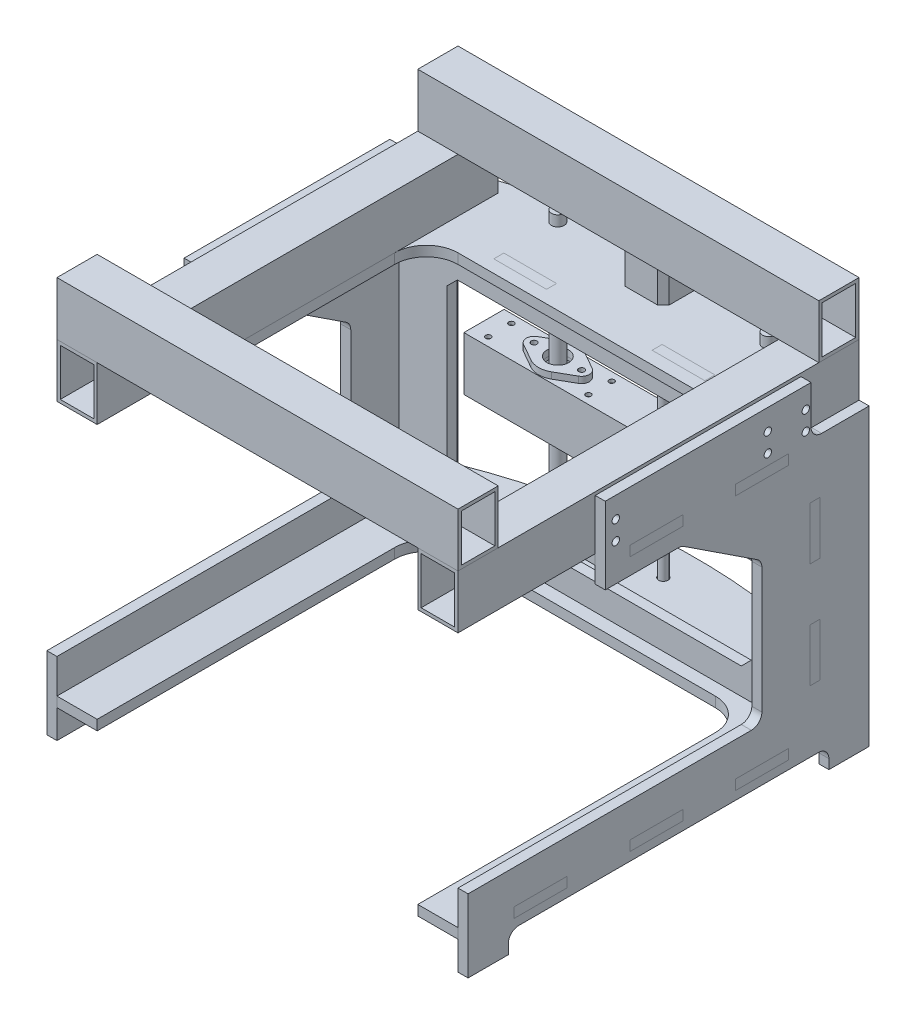
SolidWorks part; units mm, degrees
ref_plane "Front Plane" through (0, 0, 0) normal (0, 0, 1) x (1, 0, 0)
ref_plane "Top Plane" through (0, 0, 0) normal (0, 1, 0) x (1, 0, 0)
ref_plane "Right Plane" through (0, 0, 0) normal (1, 0, 0) x (0, 0, -1)
sketch "Sketch1" plane through (0, 0, 0) normal (0, 0, 1) x (1, 0, 0)
  line L0 (190, -31.5713) -> (190, 128.1143) construction
  line L1 (0, 0) -> (38.1, 0)
  line L2 (0, 0) -> (0, 50.8)
  line L3 (0, 50.8) -> (38.1, 50.8)
  line L4 (38.1, 0) -> (38.1, 50.8)
  line L5 (341.9, 0) -> (341.9, 50.8)
  line L6 (380, 50.8) -> (341.9, 50.8)
  line L7 (380, 0) -> (380, 50.8)
  line L8 (380, 0) -> (341.9, 0)
  line L9 (3.175, 47.625) -> (34.925, 47.625)
  line L10 (34.925, 3.175) -> (34.925, 47.625)
  line L11 (3.175, 3.175) -> (34.925, 3.175)
  line L12 (3.175, 3.175) -> (3.175, 47.625)
  line L13 (345.075, 3.175) -> (345.075, 47.625)
  line L14 (376.825, 47.625) -> (345.075, 47.625)
  line L15 (376.825, 3.175) -> (376.825, 47.625)
  line L16 (376.825, 3.175) -> (345.075, 3.175)
  dimension "D1" = 38.1
  dimension "D2" = 50.8
  dimension "D3" = 380
  dimension "D4" = 3.175
  dimension "D5" = 3.175
extrude "Extrude1" add sketch "Sketch1" along normal blind 380
sketch "Sketch2" plane through (0, 0, 0) normal (-1, 0, 0) x (0, 0, 1)
  line L0 (3.175, 53.975) -> (34.925, 53.975)
  line L1 (0, 50.8) -> (38.1, 50.8)
  line L2 (0, 50.8) -> (0, 101.6)
  line L3 (0, 101.6) -> (38.1, 101.6)
  line L4 (38.1, 50.8) -> (38.1, 101.6)
  line L5 (34.925, 53.975) -> (34.925, 98.425)
  line L6 (3.175, 98.425) -> (34.925, 98.425)
  line L7 (3.175, 53.975) -> (3.175, 98.425)
  line L8 (190, 50.8) -> (190, 159.3079) construction
  line L9 (380, 50.8) -> (0, 50.8) construction
  line L10 (376.825, 53.975) -> (376.825, 98.425)
  line L11 (376.825, 98.425) -> (345.075, 98.425)
  line L12 (345.075, 53.975) -> (345.075, 98.425)
  line L13 (341.9, 50.8) -> (341.9, 101.6)
  line L14 (380, 101.6) -> (341.9, 101.6)
  line L15 (380, 50.8) -> (380, 101.6)
  line L16 (380, 50.8) -> (341.9, 50.8)
  line L17 (376.825, 53.975) -> (345.075, 53.975)
  dimension "D1" = 38.1
  dimension "D2" = 50.8
  dimension "D3" = 3.175
extrude "Extrude2" add sketch "Sketch2" against normal up to surface (380 mm away) separate body up to face at (380, 25.4, 190)
sketch "Sketch3" plane through (0, 0, 0) normal (-1, 0, 0) x (0, 0, 1)
  line L0 (0, 50.8) -> (0, 0) construction
  line L1 (0, 47.8) -> (380, 47.8) construction
  line L2 (0, 47.8) -> (0, -278.4) construction
  line L3 (0, -278.4) -> (380, -278.4) construction
  line L4 (380, 47.8) -> (380, -278.4) construction
  line L5 (380, 50.8) -> (380, 0) construction
  line L6 (380, 50.8) -> (0, 50.8) construction
  line L7 (38.1, 101.6) -> (0, 101.6) construction
  line L8 (55, 47.8) -> (55, 1) construction
  line L9 (55, 1) -> (0, 1) construction
  line L10 (380, 0) -> (0, 0) construction
  line L11 (250, 47.8) -> (250, -278.4) construction
  line L12 (38.1, -278.4) -> (38.1, 47.8) construction
  line L13 (341.9, 47.8) -> (341.9, -278.4) construction
  line L14 (341.9, 101.6) -> (341.9, 50.8) construction
  line L15 (38.1, -278.4) -> (38.1, -269.35)
  line L16 (48.1, -259.35) -> (331.9, -259.35)
  line L17 (341.9, -269.35) -> (341.9, -278.4)
  line L18 (341.9, -278.4) -> (380, -278.4)
  line L19 (38.1, -278.4) -> (0, -278.4)
  line L20 (38.1, 50.8) -> (38.1, 101.6) construction
  line L21 (380, -278.4) -> (380, -209.35)
  line L22 (250, -25) -> (180.7879, -25)
  line L23 (177.8, -25) -> (177.8, -75) construction
  line L24 (111.6, -209.35) -> (380, -209.35)
  line L25 (250, -25) -> (250, 47.8)
  line L26 (55, 47.8) -> (250, 47.8)
  line L27 (55, 47.8) -> (55, 11)
  line L28 (45, 1) -> (0, 1)
  line L29 (0, 1) -> (0, -278.4)
  line L30 (177.8, -75) -> (101.6, -75) construction
  line L31 (101.6, -80.3989) -> (101.6, -199.35)
  line L32 (106.1139, -72.0381) -> (175.3018, -26.6392)
  arc A0 (45, 1) -> (55, 11) centre (45, 11) ccw
  arc A1 (106.1139, -72.0381) -> (101.6, -80.3989) centre (111.6, -80.3989) ccw
  arc A2 (180.7879, -25) -> (175.3018, -26.6392) centre (180.7879, -35) ccw
  arc A3 (111.6, -209.35) -> (101.6, -199.35) centre (111.6, -199.35) cw
  arc A4 (48.1, -259.35) -> (38.1, -269.35) centre (48.1, -269.35) ccw
  arc A5 (331.9, -259.35) -> (341.9, -269.35) centre (331.9, -269.35) cw
  point P48 (38.1, -259.35)
  point P51 (341.9, -259.35)
  dimension "D11" = 10
  dimension "D1" = 3
  dimension "D2" = 380
  dimension "D3" = 1
  dimension "D4" = 55
  dimension "D5" = 130
  dimension "D6" = 19.05
  dimension "D7" = 25
  dimension "D8" = 50
  dimension "D9" = 101.6
  dimension "D10" = 76.2
  dimension "D12" = 50
extrude "Extrude3" add sketch "Sketch3" along normal blind 9.525 separate body
sketch "Sketch7" plane through (380, 0, 0) normal (1, 0, 0) x (0, 0, -1)
  line L15 (-380, -209.35) -> (-380, -278.4)
  line L16 (-380, -278.4) -> (-341.9, -278.4)
  line L17 (-341.9, -278.4) -> (-341.9, -269.35)
  line L18 (-331.9, -259.35) -> (-48.1, -259.35)
  line L19 (-38.1, -269.35) -> (-38.1, -278.4)
  line L20 (-38.1, -278.4) -> (0, -278.4)
  line L21 (0, -278.4) -> (0, 1)
  line L22 (0, 1) -> (-45, 1)
  line L23 (-55, 11) -> (-55, 47.8)
  line L24 (-55, 47.8) -> (-250, 47.8)
  line L25 (-250, 47.8) -> (-250, -25)
  line L26 (-250, -25) -> (-180.7879, -25)
  line L27 (-175.3018, -26.6392) -> (-106.1139, -72.0381)
  line L28 (-101.6, -80.3989) -> (-101.6, -199.35)
  line L29 (-111.6, -209.35) -> (-380, -209.35)
  line L30 (-380, -209.35) -> (-380, -278.4)
  line L31 (-380, -278.4) -> (-341.9, -278.4)
  line L32 (-341.9, -278.4) -> (-341.9, -269.35)
  line L33 (-331.9, -259.35) -> (-48.1, -259.35)
  line L34 (-38.1, -269.35) -> (-38.1, -278.4)
  line L35 (-38.1, -278.4) -> (0, -278.4)
  line L36 (0, -278.4) -> (0, 1)
  line L37 (0, 1) -> (-45, 1)
  line L38 (-55, 11) -> (-55, 47.8)
  line L39 (-55, 47.8) -> (-250, 47.8)
  line L40 (-250, 47.8) -> (-250, -25)
  line L41 (-250, -25) -> (-180.7879, -25)
  line L42 (-175.3018, -26.6392) -> (-106.1139, -72.0381)
  line L43 (-101.6, -80.3989) -> (-101.6, -199.35)
  line L44 (-111.6, -209.35) -> (-380, -209.35)
  arc A6 (-331.9, -259.35) -> (-341.9, -269.35) centre (-331.9, -269.35) ccw
  arc A7 (-38.1, -269.35) -> (-48.1, -259.35) centre (-48.1, -269.35) ccw
  arc A8 (-55, 11) -> (-45, 1) centre (-45, 11) ccw
  arc A9 (-175.3018, -26.6392) -> (-180.7879, -25) centre (-180.7879, -35) ccw
  arc A10 (-101.6, -80.3989) -> (-106.1139, -72.0381) centre (-111.6, -80.3989) ccw
  arc A11 (-111.6, -209.35) -> (-101.6, -199.35) centre (-111.6, -199.35) ccw
  arc A12 (-331.9, -259.35) -> (-341.9, -269.35) centre (-331.9, -269.35) ccw
  arc A13 (-38.1, -269.35) -> (-48.1, -259.35) centre (-48.1, -269.35) ccw
  arc A14 (-55, 11) -> (-45, 1) centre (-45, 11) ccw
  arc A15 (-175.3018, -26.6392) -> (-180.7879, -25) centre (-180.7879, -35) ccw
  arc A16 (-101.6, -80.3989) -> (-106.1139, -72.0381) centre (-111.6, -80.3989) ccw
  arc A17 (-111.6, -209.35) -> (-101.6, -199.35) centre (-111.6, -199.35) ccw
  dimension "D1" = 0
extrude "Extrude5" add sketch "Sketch7" along normal blind 9.525 separate body
sketch "Sketch8" plane through (-9.525, 0, 0) normal (-1, 0, 0) x (0, 0, 1)
  line L0 (380, 0) -> (0, 0) construction
  line L1 (380, 0) -> (0, 0) construction
  line L2 (106.1139, -72.0381) -> (201.3839, -9.525) construction
  line L3 (226.3839, 0) -> (176.3839, 0)
  line L4 (226.3839, 0) -> (226.3839, -9.525)
  line L5 (226.3839, -9.525) -> (176.3839, -9.525)
  line L6 (176.3839, 0) -> (176.3839, -9.525)
  line L7 (76.3839, 0) -> (126.3839, 0)
  line L8 (76.3839, 0) -> (76.3839, -9.525)
  line L9 (76.3839, -9.525) -> (126.3839, -9.525)
  line L10 (126.3839, 0) -> (126.3839, -9.525)
  line L11 (106.1139, -72.0381) -> (175.3018, -26.6392) construction
  line L13 (176.3839, -9.525) -> (176.3839, -259.35) construction
  line L14 (48.1, -259.35) -> (331.9, -259.35) construction
  line L15 (226.3839, -9.525) -> (226.3839, -259.35) construction
  line L16 (76.3839, -9.525) -> (76.3839, -259.35) construction
  line L17 (126.3839, -9.525) -> (126.3839, -259.35) construction
  line L18 (0, -251.35) -> (380, -251.35) construction
  line L19 (0, 1) -> (0, -278.4) construction
  line L20 (380, -278.4) -> (380, -209.35) construction
  line L21 (286.3839, -251.35) -> (336.3839, -251.35)
  line L22 (76.3839, -251.35) -> (126.3839, -251.35)
  line L23 (76.3839, -251.35) -> (76.3839, -241.825)
  line L24 (76.3839, -241.825) -> (126.3839, -241.825)
  line L25 (126.3839, -251.35) -> (126.3839, -241.825)
  line L26 (176.3839, -251.35) -> (226.3839, -251.35)
  line L27 (176.3839, -251.35) -> (176.3839, -241.825)
  line L28 (176.3839, -241.825) -> (226.3839, -241.825)
  line L29 (226.3839, -251.35) -> (226.3839, -241.825)
  line L30 (286.3839, -251.35) -> (286.3839, -241.825)
  line L31 (286.3839, -241.825) -> (336.3839, -241.825)
  line L32 (336.3839, -251.35) -> (336.3839, -241.825)
  dimension "D1" = 9.525
  dimension "D2" = 50
  dimension "D3" = 50
  dimension "D4" = 50
  dimension "D5" = 8
  dimension "D6" = 9.525
  dimension "D7" = 60
  dimension "D8" = 50
extrude "Cut-Extrude1" cut sketch "Sketch8" against normal through all
sketch "Sketch9" plane through (0, 0, 0) normal (0, -1, 0) x (1, 0, 0)
  line L0 (190, -35.95) -> (190, 250) construction
  line L1 (0, 250) -> (38.1, 250)
  line L2 (0, 250) -> (0, 226.3839)
  line L3 (0, 0) -> (380, 0) construction
  line L4 (380, 250) -> (380, 226.3839)
  line L5 (-9.525, 19.05) -> (389.525, 19.05) construction
  line L6 (-9.525, 0) -> (-9.525, 38.1) construction
  line L7 (389.525, 38.1) -> (389.525, 0) construction
  line L8 (38.1, 250) -> (38.1, 98.1)
  line L9 (38.1, 380) -> (38.1, 0) construction
  line L10 (380, 38.1) -> (0, 38.1) construction
  line L11 (68.1, 68.1) -> (311.9, 68.1)
  line L12 (341.9, 380) -> (341.9, 0) construction
  line L13 (341.9, 98.1) -> (341.9, 250)
  line L14 (341.9, 250) -> (380, 250)
  line L15 (380, 176.3839) -> (380, 126.3839)
  line L16 (380, 76.3839) -> (380, 0)
  line L17 (0, 176.3839) -> (0, 126.3839)
  line L18 (0, 76.3839) -> (0, 0)
  line L19 (0, 176.3839) -> (0, 226.3839)
  line L20 (0, 226.3839) -> (-9.525, 226.3839)
  line L21 (-9.525, 226.3839) -> (-9.525, 176.3839)
  line L22 (-9.525, 176.3839) -> (0, 176.3839)
  line L24 (0, 226.3839) -> (-9.525, 226.3839)
  line L25 (-9.525, 226.3839) -> (-9.525, 176.3839)
  line L26 (-9.525, 176.3839) -> (0, 176.3839)
  line L27 (0, 76.3839) -> (0, 126.3839)
  line L28 (0, 126.3839) -> (-9.525, 126.3839)
  line L29 (-9.525, 126.3839) -> (-9.525, 76.3839)
  line L30 (-9.525, 76.3839) -> (0, 76.3839)
  line L32 (0, 126.3839) -> (-9.525, 126.3839)
  line L33 (-9.525, 126.3839) -> (-9.525, 76.3839)
  line L34 (-9.525, 76.3839) -> (0, 76.3839)
  line L35 (380, 176.3839) -> (389.525, 176.3839)
  line L36 (389.525, 176.3839) -> (389.525, 226.3839)
  line L37 (389.525, 226.3839) -> (380, 226.3839)
  line L38 (380, 226.3839) -> (380, 176.3839)
  line L39 (380, 176.3839) -> (389.525, 176.3839)
  line L40 (389.525, 176.3839) -> (389.525, 226.3839)
  line L41 (389.525, 226.3839) -> (380, 226.3839)
  line L43 (380, 76.3839) -> (389.525, 76.3839)
  line L44 (389.525, 76.3839) -> (389.525, 126.3839)
  line L45 (389.525, 126.3839) -> (380, 126.3839)
  line L46 (380, 126.3839) -> (380, 76.3839)
  line L47 (380, 76.3839) -> (389.525, 76.3839)
  line L48 (389.525, 76.3839) -> (389.525, 126.3839)
  line L49 (389.525, 126.3839) -> (380, 126.3839)
  arc A0 (0, 0) -> (380, 0) centre (190, 484.1112) ccw
  arc A1 (68.1, 68.1) -> (38.1, 98.1) centre (68.1, 98.1) cw
  arc A2 (311.9, 68.1) -> (341.9, 98.1) centre (311.9, 98.1) ccw
  point P7 (190, -35.95)
  point P27 (38.1, 68.1)
  point P28 (38.1, 38.1)
  point P31 (341.9, 38.1)
  point P49 (341.9, 68.1)
  dimension "D2" = 30
  dimension "D7" = 30
  dimension "D1" = 55
  dimension "D3" = 0
  dimension "D4" = 0
  dimension "D5" = 0
  dimension "D6" = 0
extrude "Extrude6" add sketch "Sketch9" along normal up to surface (9.525 mm away) separate body up to face at (-4.7625, -9.525, 101.3839)
sketch "Sketch10" plane through (0, -251.35, 0) normal (0, 1, 0) x (1, 0, 0)
  line L0 (0, -250) -> (0, -286.3839)
  line L1 (38.1, -250) -> (38.1, -336.3839)
  line L3 (341.9, -250) -> (341.9, -336.3839)
  line L4 (0, -336.3839) -> (0, -286.3839)
  line L5 (0, -286.3839) -> (-9.525, -286.3839)
  line L6 (-9.525, -286.3839) -> (-9.525, -336.3839)
  line L7 (-9.525, -336.3839) -> (0, -336.3839)
  line L8 (38.1, -336.3839) -> (38.1, -380)
  line L9 (0, -286.3839) -> (-9.525, -286.3839)
  line L10 (-9.525, -286.3839) -> (-9.525, -336.3839)
  line L11 (-9.525, -336.3839) -> (0, -336.3839)
  line L12 (380, -336.3839) -> (389.525, -336.3839)
  line L13 (389.525, -336.3839) -> (389.525, -286.3839)
  line L14 (389.525, -286.3839) -> (380, -286.3839)
  line L15 (380, -286.3839) -> (380, -336.3839)
  line L16 (380, -336.3839) -> (389.525, -336.3839)
  line L17 (389.525, -336.3839) -> (389.525, -286.3839)
  line L18 (389.525, -286.3839) -> (380, -286.3839)
  line L19 (38.1, -380) -> (0, -380)
  line L20 (341.9, -380) -> (341.9, 0) construction
  line L22 (380, -286.3839) -> (380, -250)
  line L23 (0, -250) -> (38.1, -250)
  line L24 (0, -226.3839) -> (0, -250)
  line L25 (-9.525, -226.3839) -> (0, -226.3839)
  line L26 (-9.525, -176.3839) -> (-9.525, -226.3839)
  line L27 (0, -176.3839) -> (-9.525, -176.3839)
  line L28 (0, -126.3839) -> (0, -176.3839)
  line L29 (-9.525, -126.3839) -> (0, -126.3839)
  line L30 (-9.525, -76.3839) -> (-9.525, -126.3839)
  line L31 (0, -76.3839) -> (-9.525, -76.3839)
  line L32 (0, 0) -> (0, -76.3839)
  line L33 (380, -76.3839) -> (380, 0)
  line L34 (389.525, -76.3839) -> (380, -76.3839)
  line L35 (389.525, -126.3839) -> (389.525, -76.3839)
  line L36 (380, -126.3839) -> (389.525, -126.3839)
  line L37 (380, -176.3839) -> (380, -126.3839)
  line L38 (389.525, -176.3839) -> (380, -176.3839)
  line L39 (389.525, -226.3839) -> (389.525, -176.3839)
  line L40 (380, -226.3839) -> (389.525, -226.3839)
  line L41 (380, -250) -> (380, -226.3839)
  line L42 (341.9, -250) -> (380, -250)
  line L43 (341.9, -98.1) -> (341.9, -250)
  line L44 (68.1, -68.1) -> (311.9, -68.1)
  line L45 (38.1, -250) -> (38.1, -98.1)
  line L46 (0, -380) -> (0, -336.3839)
  line L47 (0, -226.3839) -> (0, -250)
  line L48 (-9.525, -226.3839) -> (0, -226.3839)
  line L49 (-9.525, -176.3839) -> (-9.525, -226.3839)
  line L50 (0, -176.3839) -> (-9.525, -176.3839)
  line L51 (0, -126.3839) -> (0, -176.3839)
  line L52 (-9.525, -126.3839) -> (0, -126.3839)
  line L53 (-9.525, -76.3839) -> (-9.525, -126.3839)
  line L54 (0, -76.3839) -> (-9.525, -76.3839)
  line L55 (0, 0) -> (0, -76.3839)
  line L56 (380, -76.3839) -> (380, 0)
  line L57 (389.525, -76.3839) -> (380, -76.3839)
  line L58 (389.525, -126.3839) -> (389.525, -76.3839)
  line L59 (380, -126.3839) -> (389.525, -126.3839)
  line L60 (380, -176.3839) -> (380, -126.3839)
  line L61 (389.525, -176.3839) -> (380, -176.3839)
  line L62 (389.525, -226.3839) -> (389.525, -176.3839)
  line L63 (380, -226.3839) -> (389.525, -226.3839)
  line L64 (380, -250) -> (380, -226.3839)
  line L65 (341.9, -336.3839) -> (341.9, -380)
  line L66 (341.9, -98.1) -> (341.9, -250)
  line L67 (68.1, -68.1) -> (311.9, -68.1)
  line L68 (38.1, -250) -> (38.1, -98.1)
  line L69 (380, -380) -> (0, -380) construction
  line L70 (341.9, -380) -> (380, -380)
  line L71 (380, -380) -> (380, -336.3839)
  arc A3 (380, 0) -> (0, 0) centre (190, -484.1112) ccw
  arc A4 (341.9, -98.1) -> (311.9, -68.1) centre (311.9, -98.1) ccw
  arc A5 (68.1, -68.1) -> (38.1, -98.1) centre (68.1, -98.1) ccw
  arc A6 (380, 0) -> (0, 0) centre (190, -484.1112) ccw
  arc A7 (341.9, -98.1) -> (311.9, -68.1) centre (311.9, -98.1) ccw
  arc A8 (68.1, -68.1) -> (38.1, -98.1) centre (68.1, -98.1) ccw
  dimension "D1" = 0
  dimension "D2" = 0
  dimension "D3" = 0
extrude "Extrude7" add sketch "Sketch10" along normal up to surface (9.525 mm away) separate body up to face at (-4.7625, -241.825, 101.3839)
sketch "Sketch11" plane through (0, 0, 0) normal (0, 1, 0) x (1, 0, 0)
  line L0 (190, -380) -> (190, 35.95) construction
  line L1 (380, -380) -> (0, -380) construction
  line L2 (168.85, 4.6) -> (211.15, 4.6) construction
  line L3 (168.85, 25.75) -> (211.15, 25.75) construction
  line L4 (168.85, 25.75) -> (168.85, -16.55) construction
  line L5 (168.85, -16.55) -> (211.15, -16.55) construction
  line L6 (211.15, 25.75) -> (211.15, -16.55) construction
  line L7 (174.5, 20.1) -> (205.5, 20.1) construction
  line L8 (205.5, 20.1) -> (205.5, -10.9) construction
  line L9 (174.5, -10.9) -> (205.5, -10.9) construction
  line L10 (174.5, 20.1) -> (174.5, -10.9) construction
  line L11 (0, -19.05) -> (380, -19.05) construction
  line L17 (380, -38.1) -> (380, 0)
  line L18 (380, 0) -> (0, 0)
  line L19 (0, 0) -> (0, -38.1)
  line L20 (0, -38.1) -> (380, -38.1)
  line L21 (380, -38.1) -> (380, 0) construction
  line L22 (380, 0) -> (0, 0) construction
  line L23 (0, 0) -> (0, -38.1) construction
  line L24 (0, -38.1) -> (380, -38.1) construction
  arc A0 (380, 0) -> (0, 0) centre (190, -484.1112) ccw construction
  circle A1 centre (190, 4.6) radius 12
  circle A2 centre (90, 4.6) radius 6
  circle A3 centre (290, 4.6) radius 6
  point P11 (190, 25.75)
  dimension "D5" = 24
  dimension "D6" = 12
  dimension "D1" = 42.3
  dimension "D2" = 31
  dimension "D3" = 0
  dimension "D4" = 2.5
  dimension "D7" = 200
extrude "Cut-Extrude2" cut sketch "Sketch11" against normal up to next (9.525 mm away)
sketch "Sketch12" plane through (0, -241.825, 0) normal (0, 1, 0) x (1, 0, 0)
  circle A0 centre (90, 4.6) radius 6 construction
  circle A1 centre (190, 4.6) radius 12 construction
  circle A2 centre (290, 4.6) radius 6 construction
  circle A3 centre (90, 4.6) radius 6
  circle A4 centre (190, 4.6) radius 12 construction
  circle A5 centre (290, 4.6) radius 6
  circle A6 centre (190, 4.6) radius 4.5
  dimension "D1" = 9
extrude "Cut-Extrude3" cut sketch "Sketch12" against normal up to next (9.525 mm away)
sketch "Sketch13" plane through (0, 0, 0) normal (0, 1, 0) x (1, 0, 0)
  line L0 (174.5, 25.6) -> (169, 20.1)
  line L1 (174.5, 25.6) -> (205.5, 25.6)
  line L2 (169, 20.1) -> (169, -10.9)
  line L3 (174.5, -16.4) -> (205.5, -16.4)
  line L4 (211, 20.1) -> (211, -10.9)
  line L5 (205.5, 25.6) -> (211, 20.1)
  line L6 (211, -10.9) -> (205.5, -16.4)
  line L7 (169, -10.9) -> (174.5, -16.4)
  line L8 (169, 4.6) -> (211, 4.6) construction
  circle A4 centre (190, 4.6) radius 4.5 construction
  point P0 (169, 25.6)
  point P1 (211, -16.4)
  point P2 (169, -16.4)
  point P3 (211, 25.6)
  point P14 (190, 4.6)
  dimension "D1" = 42
  dimension "D4" = 5.5
  dimension "D5" = 5.5
  dimension "D6" = 5.5
  dimension "D7" = 5.5
extrude "Extrude8" add sketch "Sketch13" along normal blind 48 separate body
sketch "Sketch14" plane through (0, 0, 0) normal (0, 1, 0) x (1, 0, 0)
  circle A0 centre (90, 4.6) radius 6 construction
  circle A1 centre (290, 4.6) radius 6 construction
  circle A2 centre (90, 4.6) radius 6
  circle A3 centre (290, 4.6) radius 6
extrude "Extrude9" add sketch "Sketch14" along normal blind 10 and the other way offset from surface (259.35 mm away) 8 separate body other way up to face at (190, -251.35, -0.1)
sketch "Sketch15" plane through (0, -251.35, 0) normal (0, -1, 0) x (1, 0, 0)
  circle A0 centre (190, -4.6) radius 4
  dimension "D1" = 8
extrude "Extrude10" add sketch "Sketch15" against normal up to surface (251.35 mm away) separate body up to face at (190, 0, -4.6)
sketch "Sketch16" plane through (0, 0, 0) normal (0, 1, 0) x (1, 0, 0)
  line L0 (38.1, -56.1) -> (341.9, -56.1) construction
  line L1 (38.1, -380) -> (38.1, 0) construction
  line L2 (341.9, -380) -> (341.9, 0) construction
  line L4 (311.9, -68.1) -> (68.1, -68.1) construction
  line L5 (190, 0) -> (190, -380) construction
  line L6 (90, -56.1) -> (140, -56.1)
  line L7 (90, -56.1) -> (90, -46.575)
  line L8 (90, -46.575) -> (140, -46.575)
  line L9 (140, -56.1) -> (140, -46.575)
  line L10 (380, 0) -> (0, 0) construction
  line L11 (380, -380) -> (0, -380) construction
  line L12 (240, -56.1) -> (240, -46.575)
  line L13 (290, -56.1) -> (240, -56.1)
  line L14 (290, -56.1) -> (290, -46.575)
  line L15 (290, -46.575) -> (240, -46.575)
  dimension "D1" = 12
  dimension "D2" = 50
  dimension "D3" = 9.525
  dimension "D4" = 50
extrude "Cut-Extrude4" cut sketch "Sketch16" against normal through all
sketch "Sketch17" plane through (-9.525, 0, 0) normal (-1, 0, 0) x (0, 0, 1)
  line L0 (46.575, -9.525) -> (46.575, -241.825) construction
  line L1 (56.1, -9.525) -> (56.1, -241.825) construction
  line L2 (46.575, -125.675) -> (91.0114, -125.675) construction
  line L3 (56.1, -100.675) -> (56.1, -50.675)
  line L4 (46.575, -9.525) -> (56.1, -9.525)
  line L5 (56.1, -9.525) -> (56.1, 0)
  line L6 (56.1, 0) -> (46.575, 0)
  line L7 (46.575, 0) -> (46.575, -9.525)
  line L8 (46.575, -9.525) -> (56.1, -9.525) construction
  line L9 (56.1, -9.525) -> (56.1, 0) construction
  line L10 (56.1, 0) -> (46.575, 0) construction
  line L11 (46.575, 0) -> (46.575, -9.525) construction
  line L12 (46.575, -50.675) -> (56.1, -50.675)
  line L13 (46.575, -100.675) -> (46.575, -50.675)
  line L14 (46.575, -100.675) -> (56.1, -100.675)
  line L15 (46.575, -150.675) -> (56.1, -150.675)
  line L16 (46.575, -150.675) -> (46.575, -200.675)
  line L17 (46.575, -200.675) -> (56.1, -200.675)
  line L18 (56.1, -150.675) -> (56.1, -200.675)
  line L22 (56.1, -251.35) -> (56.1, -241.825)
  line L23 (56.1, -241.825) -> (46.575, -241.825)
  line L24 (46.575, -241.825) -> (46.575, -251.35)
  line L25 (46.575, -251.35) -> (56.1, -251.35)
  line L26 (56.1, -251.35) -> (56.1, -241.825) construction
  line L27 (56.1, -241.825) -> (46.575, -241.825) construction
  line L28 (46.575, -241.825) -> (46.575, -251.35) construction
  line L29 (46.575, -251.35) -> (56.1, -251.35) construction
  dimension "D3" = 50
  dimension "D4" = 50
  dimension "D1" = 0
  dimension "D2" = 0
extrude "Cut-Extrude5" cut sketch "Sketch17" against normal through all
sketch "Sketch18" plane through (0, 0, 46.575) normal (0, 0, 1) x (1, 0, 0)
  line L0 (0, -9.525) -> (90, -9.525)
  line L1 (380, -9.525) -> (380, -50.675)
  line L2 (380, -241.825) -> (290, -241.825)
  line L3 (0, -241.825) -> (0, -200.675)
  line L4 (380, -100.675) -> (380, -150.675)
  line L5 (380, -200.675) -> (380, -241.825)
  line L6 (240, -241.825) -> (140, -241.825)
  line L7 (90, -241.825) -> (0, -241.825)
  line L8 (240, -9.525) -> (290, -9.525)
  line L9 (290, -9.525) -> (290, 0)
  line L10 (290, 0) -> (240, 0)
  line L11 (240, 0) -> (240, -9.525)
  line L13 (290, -9.525) -> (290, 0)
  line L14 (290, 0) -> (240, 0)
  line L15 (240, 0) -> (240, -9.525)
  line L16 (90, -9.525) -> (140, -9.525)
  line L17 (140, -9.525) -> (140, 0)
  line L18 (140, 0) -> (90, 0)
  line L19 (90, 0) -> (90, -9.525)
  line L20 (290, -9.525) -> (380, -9.525)
  line L21 (140, -9.525) -> (140, 0)
  line L22 (140, 0) -> (90, 0)
  line L23 (90, 0) -> (90, -9.525)
  line L24 (0, -100.675) -> (0, -50.675)
  line L25 (0, -50.675) -> (-9.525, -50.675)
  line L26 (-9.525, -50.675) -> (-9.525, -100.675)
  line L27 (-9.525, -100.675) -> (0, -100.675)
  line L28 (140, -9.525) -> (240, -9.525)
  line L29 (0, -50.675) -> (-9.525, -50.675)
  line L30 (-9.525, -50.675) -> (-9.525, -100.675)
  line L31 (-9.525, -100.675) -> (0, -100.675)
  line L32 (0, -200.675) -> (0, -150.675)
  line L33 (0, -150.675) -> (-9.525, -150.675)
  line L34 (-9.525, -150.675) -> (-9.525, -200.675)
  line L35 (-9.525, -200.675) -> (0, -200.675)
  line L36 (0, -50.675) -> (0, -9.525)
  line L37 (0, -150.675) -> (-9.525, -150.675)
  line L38 (-9.525, -150.675) -> (-9.525, -200.675)
  line L39 (-9.525, -200.675) -> (0, -200.675)
  line L40 (140, -251.35) -> (140, -241.825)
  line L41 (140, -241.825) -> (90, -241.825)
  line L42 (90, -241.825) -> (90, -251.35)
  line L43 (90, -251.35) -> (140, -251.35)
  line L44 (140, -251.35) -> (140, -241.825)
  line L45 (0, -150.675) -> (0, -100.675)
  line L46 (90, -241.825) -> (90, -251.35)
  line L47 (90, -251.35) -> (140, -251.35)
  line L48 (290, -251.35) -> (290, -241.825)
  line L49 (290, -241.825) -> (240, -241.825)
  line L50 (240, -241.825) -> (240, -251.35)
  line L51 (240, -251.35) -> (290, -251.35)
  line L52 (290, -251.35) -> (290, -241.825)
  line L54 (240, -241.825) -> (240, -251.35)
  line L55 (240, -251.35) -> (290, -251.35)
  line L56 (380, -200.675) -> (389.525, -200.675)
  line L57 (389.525, -200.675) -> (389.525, -150.675)
  line L58 (389.525, -150.675) -> (380, -150.675)
  line L59 (380, -150.675) -> (380, -200.675)
  line L60 (380, -200.675) -> (389.525, -200.675)
  line L61 (389.525, -200.675) -> (389.525, -150.675)
  line L62 (389.525, -150.675) -> (380, -150.675)
  line L64 (380, -100.675) -> (389.525, -100.675)
  line L65 (389.525, -100.675) -> (389.525, -50.675)
  line L66 (389.525, -50.675) -> (380, -50.675)
  line L67 (380, -50.675) -> (380, -100.675)
  line L68 (380, -100.675) -> (389.525, -100.675)
  line L69 (389.525, -100.675) -> (389.525, -50.675)
  line L70 (389.525, -50.675) -> (380, -50.675)
  dimension "D1" = 0
  dimension "D2" = 0
  dimension "D3" = 0
  dimension "D4" = 0
  dimension "D5" = 0
  dimension "D6" = 0
  dimension "D7" = 0
  dimension "D8" = 0
extrude "Extrude11" add sketch "Sketch18" along normal up to surface (9.525 mm away) separate body up to face at (-4.7625, -175.675, 56.1)
sketch "Sketch20" plane through (0, 0, 46.575) normal (0, 0, -1) x (-1, 0, 0)
  line L0 (-190, 0) -> (-190, -251.35) construction
  line L3 (0, 0) -> (-380, 0) construction
  line L6 (-380, -251.35) -> (0, -251.35) construction
  line L10 (-264.5, -34.525) -> (-255.5, -34.525)
  line L11 (-264.5, -34.525) -> (-264.5, -216.825)
  line L12 (-264.5, -216.825) -> (-255.5, -216.825)
  line L13 (-255.5, -34.525) -> (-255.5, -216.825)
  line L15 (-260, -34.525) -> (-260, -216.825) construction
  line L17 (-334.5, -34.525) -> (-325.5, -34.525)
  line L18 (-334.5, -34.525) -> (-334.5, -216.825)
  line L19 (-334.5, -216.825) -> (-325.5, -216.825)
  line L20 (-325.5, -34.525) -> (-325.5, -216.825)
  line L21 (-330, -34.525) -> (-330, -216.825) construction
  line L22 (-54.5, -34.525) -> (-54.5, -216.825)
  line L23 (-45.5, -216.825) -> (-54.5, -216.825)
  line L24 (-45.5, -34.525) -> (-45.5, -216.825)
  line L25 (-45.5, -34.525) -> (-54.5, -34.525)
  line L26 (-124.5, -34.525) -> (-124.5, -216.825)
  line L27 (-115.5, -216.825) -> (-124.5, -216.825)
  line L28 (-115.5, -34.525) -> (-115.5, -216.825)
  line L29 (-115.5, -34.525) -> (-124.5, -34.525)
  line L30 (-380, -9.525) -> (0, -9.525) construction
  line L31 (-290, -241.825) -> (-380, -241.825) construction
  line L32 (-190, -125.675) -> (-138.6415, -125.675) construction
  line L33 (-200, -50.675) -> (-180, -50.675)
  line L34 (-215, -65.675) -> (-215, -185.675)
  line L35 (-200, -200.675) -> (-180, -200.675)
  line L36 (-165, -65.675) -> (-165, -185.675)
  arc A0 (-200, -50.675) -> (-215, -65.675) centre (-200, -65.675) ccw
  arc A1 (-165, -65.675) -> (-180, -50.675) centre (-180, -65.675) ccw
  arc A2 (-180, -200.675) -> (-165, -185.675) centre (-180, -185.675) ccw
  arc A3 (-200, -200.675) -> (-215, -185.675) centre (-200, -185.675) cw
  point P38 (-215, -50.675)
  point P45 (-215, -200.675)
  dimension "D9" = 15
  dimension "D1" = 9
  dimension "D2" = 9
  dimension "D3" = 70
  dimension "D4" = 70
  dimension "D5" = 25
  dimension "D6" = 25
  dimension "D7" = 50
  dimension "D8" = 150
extrude "Cut-Extrude7" cut sketch "Sketch20" against normal through all
sketch "Sketch21" plane through (-9.525, 0, 0) normal (-1, 0, 0) x (0, 0, 1)
  line L0 (380, 0) -> (0, 0) construction
  line L1 (380, 0) -> (0, 0) construction
  line L2 (60, 50.8) -> (60, 0) construction
  line L3 (380, 50.8) -> (0, 50.8) construction
  line L4 (96, 50.8) -> (96, 0) construction
  line L5 (0, 28) -> (380, 28) construction
  line L6 (0, 50.8) -> (0, 0) construction
  line L7 (380, 50.8) -> (380, 0) construction
  line L8 (0, 10) -> (380, 10) construction
  line L9 (240, 50.8) -> (240, 0) construction
  circle A0 centre (60, 28) radius 3.5
  circle A1 centre (60, 10) radius 3.5
  circle A2 centre (96, 28) radius 3.5
  circle A3 centre (96, 10) radius 3.5
  circle A4 centre (240, 28) radius 3.5
  circle A5 centre (240, 10) radius 3.5
  dimension "D1" = 7
  dimension "D2" = 10
  dimension "D3" = 18
  dimension "D4" = 60
  dimension "D5" = 36
  dimension "D6" = 180
extrude "Cut-Extrude8" cut sketch "Sketch21" against normal through all
sketch "Sketch22" plane through (0, 0, 56.1) normal (0, 0, 1) x (1, 0, 0)
  line L1 (45.5, -34.525) -> (334.5, -34.525)
  line L2 (45.5, -34.525) -> (45.5, -216.825)
  line L3 (45.5, -216.825) -> (334.5, -216.825)
  line L4 (334.5, -34.525) -> (334.5, -216.825)
extrude "Cut-Extrude9" cut sketch "Sketch22" against normal through all
chamfer "Chamfer1" distance 10 angle 45 4 edges at (45.5, -216.825, 51.3375) (334.5, -216.825, 51.3375) (334.5, -34.525, 51.3375) (45.5, -34.525, 51.3375)
ref_point "Point1"
ref_plane "Mid-Plane" through (190, 0, 0) normal (-1, 0, 0) x (0, 0, 1)
sketch "Sketch23" plane through (190, 0, 0) normal (-1, 0, 0) x (0, 0, 1)
  line L0 (-4.6, 10) -> (-4.6, -262.0924) construction
  line L1 (1.4, 10) -> (-10.6, 10) construction
  line L2 (-20.475, -119.4974) -> (11.275, -119.4974)
  line L3 (-23.65, -116.3224) -> (14.45, -116.3224)
  line L4 (-23.65, -116.3224) -> (-23.65, -167.1224)
  line L5 (-23.65, -167.1224) -> (14.45, -167.1224)
  line L6 (14.45, -116.3224) -> (14.45, -167.1224)
  line L7 (11.275, -119.4974) -> (11.275, -163.9474)
  line L8 (-20.475, -163.9474) -> (11.275, -163.9474)
  line L9 (-20.475, -119.4974) -> (-20.475, -163.9474)
  dimension "D1" = 50.8
  dimension "D2" = 38.1
  dimension "D3" = 3.175
extrude "Extrude12" add sketch "Sketch23" along normal mid plane 340 separate body
sketch "Sketch28" plane through (0, -116.3224, 0) normal (0, 1, 0) x (1, 0, 0)
  line L0 (190, 23.65) -> (190, -17.3758) construction
  line L1 (20, 23.65) -> (360, 23.65) construction
  line L2 (290, 23.65) -> (290, -14.45) construction
  line L3 (20, -14.45) -> (360, -14.45) construction
  line L4 (90, 23.65) -> (90, -14.45) construction
  line L5 (360, 4.6) -> (20, 4.6) construction
  line L6 (360, -14.45) -> (360, 23.65) construction
  line L7 (20, -14.45) -> (20, 23.65) construction
  line L9 (290.5, -6) -> (289.5, -6)
  line L10 (290.5, -6) -> (290.5, 15.2) construction
  line L11 (290.5, 15.2) -> (289.5, 15.2)
  line L12 (289.5, -6) -> (289.5, 15.2) construction
  circle A0 centre (290, 4.6) radius 6 construction
  circle A1 centre (90, 4.6) radius 6 construction
  circle A2 centre (290, 4.6) radius 6 construction
  circle A3 centre (90, 4.6) radius 6 construction
  circle A4 centre (90, 4.6) radius 10.6
  arc A5 (289.5, 15.2) -> (289.5, -6) centre (289.5, 4.6) ccw
  arc A6 (290.5, -6) -> (290.5, 15.2) centre (290.5, 4.6) ccw
  circle A7 centre (312.5, 4.6) radius 2
  circle A8 centre (267.5, 4.6) radius 2
  circle A9 centre (67.5, 4.6) radius 2
  circle A10 centre (112.5, 4.6) radius 2
  circle A11 centre (190, 4.6) radius 14
  dimension "D1" = 21.2
  dimension "D4" = 4
  dimension "D6" = 28
  dimension "D2" = 1
  dimension "D3" = 21.2
  dimension "D5" = 45
extrude "Cut-Extrude13" cut sketch "Sketch28" against normal up to next (3.175 mm away)
sketch "Sketch29" plane through (0, -167.1224, 0) normal (0, -1, 0) x (1, 0, 0)
  line L0 (290, -23.65) -> (290, 14.45) construction
  line L1 (20, -23.65) -> (360, -23.65) construction
  line L2 (20, 14.45) -> (360, 14.45) construction
  line L3 (190, -23.65) -> (190, 14.45) construction
  line L4 (360, -4.6) -> (20, -4.6) construction
  line L5 (360, -23.65) -> (360, 14.45) construction
  line L6 (20, -23.65) -> (20, 14.45) construction
  circle A0 centre (190, -4.6) radius 4 construction
  circle A1 centre (90, -4.6) radius 6 construction
  circle A2 centre (290, -4.6) radius 6 construction
  circle A3 centre (190, -4.6) radius 4 construction
  circle A4 centre (90, -4.6) radius 6 construction
  circle A5 centre (290, -4.6) radius 6 construction
  circle A6 centre (290, -4.6) radius 11
  circle A7 centre (312.5, -4.6) radius 2
  circle A8 centre (190, -4.6) radius 8
  circle A9 centre (267.5, -4.6) radius 2
  circle A10 centre (112.5, -4.6) radius 2
  circle A11 centre (90, -4.6) radius 11
  circle A12 centre (67.5, -4.6) radius 2
  circle A13 centre (212.5, -4.6) radius 2
  circle A14 centre (167.5, -4.6) radius 2
  dimension "D1" = 22
  dimension "D2" = 16
  dimension "D3" = 4
  dimension "D5" = 4
  dimension "D4" = 45
  dimension "D6" = 45
extrude "Cut-Extrude14" cut sketch "Sketch29" against normal up to next (3.175 mm away)
sketch "Sketch30" plane through (0, -116.3224, 0) normal (0, 1, 0) x (1, 0, 0)
  line L0 (190, 23.65) -> (190, -14.45) construction
  line L1 (20, 23.65) -> (360, 23.65) construction
  line L2 (20, -14.45) -> (360, -14.45) construction
  line L3 (360, 4.6) -> (20, 4.6) construction
  line L4 (360, -14.45) -> (360, 23.65) construction
  line L5 (20, -14.45) -> (20, 23.65) construction
  line L6 (250, -14.45) -> (250, 23.65) construction
  line L7 (345, -14.45) -> (345, 23.65) construction
  line L8 (360, -6.4) -> (20, -6.4) construction
  circle A0 centre (345, -6.4) radius 2.5
  circle A1 centre (250, -6.4) radius 2.5
  circle A2 centre (250, 15.6) radius 2.5
  circle A3 centre (345, 15.6) radius 2.5
  circle A4 centre (35, 15.6) radius 2.5
  circle A5 centre (130, 15.6) radius 2.5
  circle A6 centre (130, -6.4) radius 2.5
  circle A7 centre (35, -6.4) radius 2.5
  dimension "D1" = 5
  dimension "D2" = 60
  dimension "D3" = 95
  dimension "D4" = 22
extrude "Cut-Extrude15" cut sketch "Sketch30" against normal through all
sketch "Sketch31" plane through (0, -9.525, 0) normal (0, -1, 0) x (1, 0, 0)
  line L0 (315.5897, -4.6) -> (59.5045, -4.6) construction
  line L1 (190, -35.95) -> (190, 27.2679) construction
  line L3 (205.5, -20.1) -> (174.5, -20.1) construction
  line L4 (205.5, -20.1) -> (205.5, 10.9) construction
  line L5 (205.5, 10.9) -> (174.5, 10.9) construction
  line L6 (174.5, -20.1) -> (174.5, 10.9) construction
  arc A0 (0, 0) -> (380, 0) centre (190, 484.1112) ccw construction
  circle A1 centre (174.5, -20.1) radius 2
  circle A2 centre (205.5, -20.1) radius 2
  circle A3 centre (205.5, 10.9) radius 2
  circle A4 centre (174.5, 10.9) radius 2
  point P0 (190, -4.6)
  dimension "D2" = 4
  dimension "D1" = 31
extrude "Cut-Extrude16" cut sketch "Sketch31" against normal up to surface (9.525 mm away)
sketch "Sketch32" plane through (0, -116.3224, 0) normal (0, 1, 0) x (1, 0, 0)
  line L0 (112.5, 4.6) -> (67.5, 4.6) construction
  line L1 (90, 23.65) -> (90, -14.45) construction
  line L2 (116.0598, -1.8386) -> (99.8303, -11.094)
  line L3 (63.9402, -1.8386) -> (80.1697, -11.094)
  line L4 (20, 23.65) -> (360, 23.65) construction
  line L5 (20, -14.45) -> (360, -14.45) construction
  line L6 (116.0598, 11.0386) -> (99.8303, 20.294)
  line L7 (63.9402, 11.0386) -> (80.1697, 20.294)
  circle A1 centre (90, 4.6) radius 10.6 construction
  arc A2 (80.1697, -11.094) -> (99.8303, -11.094) centre (90, 6.1436) ccw
  arc A3 (116.0598, 11.0386) -> (116.0598, -1.8386) centre (112.388, 4.6) cw
  arc A4 (80.1697, 20.294) -> (99.8303, 20.294) centre (90, 3.0564) cw
  arc A5 (63.9402, -1.8386) -> (63.9402, 11.0386) centre (67.612, 4.6) cw
  circle A6 centre (112.5, 4.6) radius 2.75
  circle A7 centre (67.5, 4.6) radius 2.75
  circle A8 centre (90, 4.6) radius 10.35
  point P9 (90, 4.6)
  point P17 (90, -16.7)
  point P20 (127.35, 4.6)
  point P23 (90, 25.9)
  point P26 (52.65, 4.6)
  point P27 (90, -13.7)
  point P28 (119.8, 4.6)
  point P29 (60.2, 4.6)
  point P30 (90, 22.9)
  dimension "D3" = 36.6
  dimension "D5" = 5.5
  dimension "D6" = 20.7
  dimension "D1" = 74.7
  dimension "D2" = 42.6
  dimension "D4" = 59.6
extrude "Extrude13" add sketch "Sketch32" along normal blind 6 separate body
sketch "Sketch33" plane through (0, -167.1224, 0) normal (0, -1, 0) x (1, 0, 0)
  line L0 (212.5, -4.6) -> (167.5, -4.6) construction
  line L1 (190, -23.65) -> (190, 14.45) construction
  line L2 (20, -23.65) -> (360, -23.65) construction
  line L3 (20, 14.45) -> (360, 14.45) construction
  line L4 (216.0598, -11.0386) -> (194.9539, -23.0749)
  line L5 (163.9402, -11.0386) -> (185.0461, -23.0749)
  line L6 (216.0598, 1.8386) -> (194.9539, 13.8749)
  line L7 (163.9402, 1.8386) -> (185.0461, 13.8749)
  line L9 (186.2905, -11.025) -> (193.7095, -11.025)
  line L10 (193.7095, -11.025) -> (197.419, -4.6)
  line L11 (197.419, -4.6) -> (193.7095, 1.825)
  line L12 (193.7095, 1.825) -> (186.2905, 1.825)
  line L13 (186.2905, 1.825) -> (182.581, -4.6)
  line L14 (182.581, -4.6) -> (186.2905, -11.025)
  arc A0 (185.0461, -23.0749) -> (194.9539, -23.0749) centre (190, -14.3882) ccw
  arc A1 (163.9402, 1.8386) -> (163.9402, -11.0386) centre (167.612, -4.6) ccw
  arc A2 (194.9539, 13.8749) -> (185.0461, 13.8749) centre (190, 5.1882) ccw
  arc A3 (216.0598, -11.0386) -> (216.0598, 1.8386) centre (212.388, -4.6) ccw
  circle A4 centre (212.5, -4.6) radius 2.75
  circle A5 centre (167.5, -4.6) radius 2.75
  circle A6 centre (190, -4.6) radius 6.425 construction
  point P16 (190, -25.9)
  point P19 (152.65, -4.6)
  point P22 (190, 16.7)
  point P25 (227.35, -4.6)
  point P26 (219.8, -4.6)
  point P27 (160.2, -4.6)
  point P28 (190, -24.3882)
  point P29 (190, 15.1882)
  dimension "D3" = 39.5764
  dimension "D5" = 5.5
  dimension "D1" = 74.7
  dimension "D2" = 42.6
  dimension "D4" = 59.6
  dimension "D6" = 12.85
extrude "Extrude14" add sketch "Sketch33" along normal blind 6 separate body
